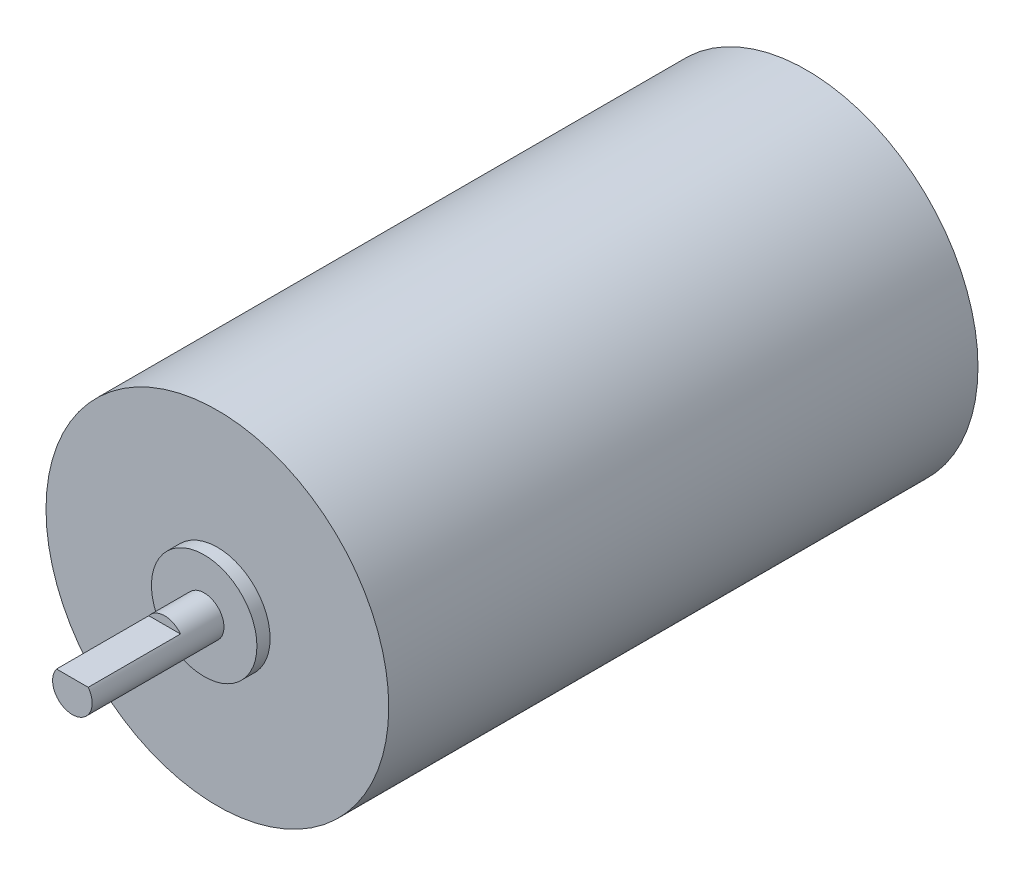
SolidWorks part; units mm, degrees
ref_plane "Plan de face" through (0, 0, 0) normal (0, 0, 1) x (1, 0, 0)
ref_plane "Plan de dessus" through (0, 0, 0) normal (0, 1, 0) x (1, 0, 0)
ref_plane "Plan de droite" through (0, 0, 0) normal (1, 0, 0) x (0, 0, -1)
sketch "Esquisse1" plane through (0, 0, 0) normal (0, 0, 1) x (1, 0, 0)
  circle A0 centre (0, 0) radius 13
  dimension "D1" = 26
extrude "Boss.-Extru.1" add sketch "Esquisse1" along normal blind 44.7
sketch "Esquisse2" plane through (0, 0, 44.7) normal (0, 0, 1) x (1, 0, 0)
  circle A0 centre (0, 0) radius 4
extrude "Boss.-Extru.2" add sketch "Esquisse2" along normal blind 1
sketch "Esquisse3" plane through (0, 0, 45.7) normal (0, 0, 1) x (1, 0, 0)
  circle A0 centre (0, 0) radius 1.5
  dimension "D1" = 3
extrude "Boss.-Extru.3" add sketch "Esquisse3" along normal blind 10
sketch "Esquisse4" plane through (0, 0, 55.7) normal (0, 0, 1) x (1, 0, 0)
  line L0 (-1.2009, 0.8988) -> (1.2009, 0.8988)
  circle A0 centre (0, 0) radius 1.5 construction
  arc A1 (-1.2009, 0.8988) -> (1.2009, 0.8988) centre (0, 0) cw
extrude "Enlèv. mat.-Extru.1" cut sketch "Esquisse4" against normal blind 7
